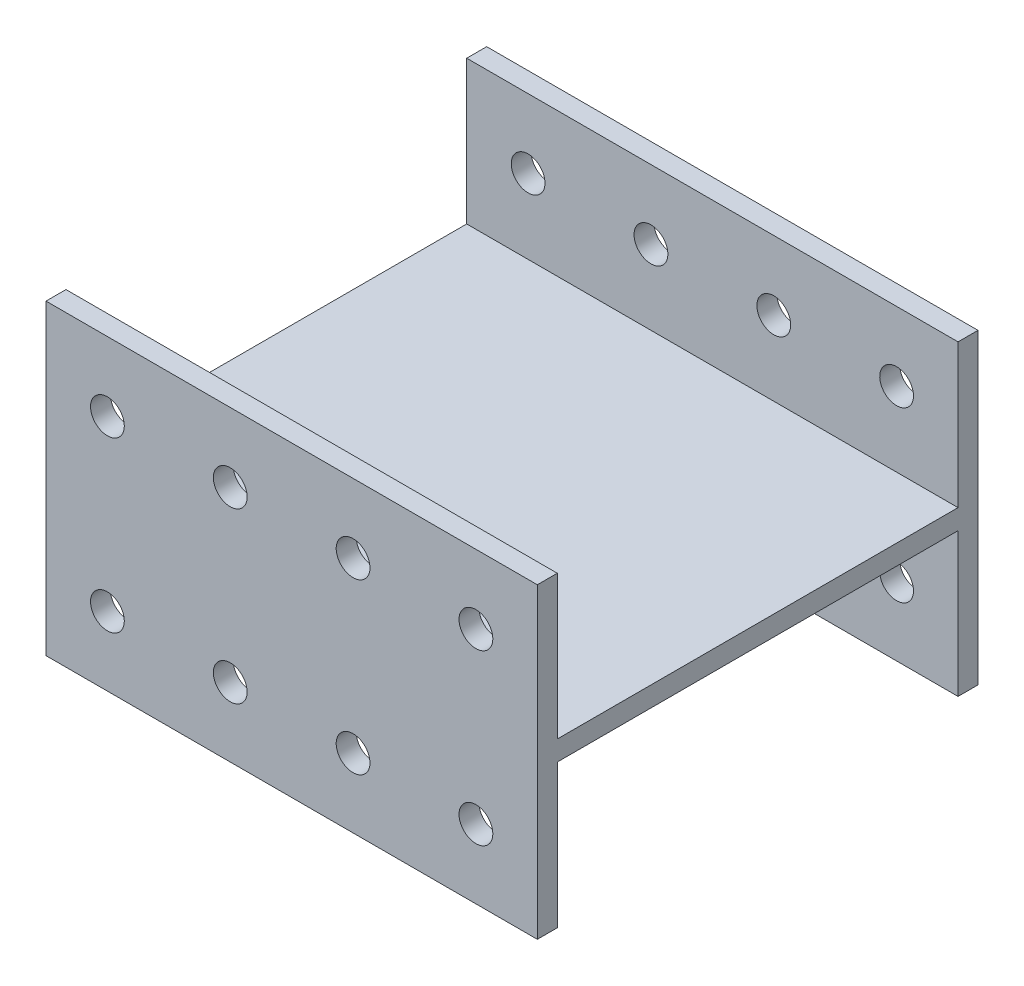
SolidWorks part; units mm, degrees
ref_plane "前视基准面" through (0, 0, 0) normal (0, 0, 1) x (1, 0, 0)
ref_plane "上视基准面" through (0, 0, 0) normal (0, 1, 0) x (1, 0, 0)
ref_plane "右视基准面" through (0, 0, 0) normal (1, 0, 0) x (0, 0, -1)
sketch "草图1" plane through (0, 0, 0) normal (0, 0, 1) x (1, 0, 0)
  line L1 (0, 200) -> (320, 200)
  line L2 (0, 200) -> (0, 0)
  line L3 (0, 0) -> (320, 0)
  line L4 (320, 200) -> (320, 0)
  dimension "D1" = 320
  dimension "D2" = 200
extrude "拉伸1" add sketch "草图1" along normal blind 287
sketch "草图2" plane through (0, 0, 287) normal (0, 0, 1) x (1, 0, 0)
  line L0 (0, 0) -> (320, 0) construction
  line L1 (0, 200) -> (0, 0) construction
  circle A0 centre (40, 45) radius 11
  dimension "D1" = 45
  dimension "D2" = 40
extrude "切除-拉伸1" cut sketch "草图2" against normal through all
pattern_linear "阵列(线性)1" count 4 spacing 80 along (1, 0, 0) count 2 spacing 110 along (0, 1, 0) of "切除-拉伸1"
sketch "草图6" plane through (0, 0, 0) normal (-1, 0, 0) x (0, 0, 1)
  line L1 (13, 200) -> (274, 200)
  line L2 (13, 200) -> (13, 106.5)
  line L3 (13, 106.5) -> (274, 106.5)
  line L4 (274, 200) -> (274, 106.5)
  line L7 (13, 0) -> (274, 0)
  line L8 (13, 0) -> (13, 93.5)
  line L9 (13, 93.5) -> (274, 93.5)
  line L10 (274, 0) -> (274, 93.5)
  line L12 (287, 200) -> (287, 0) construction
  line L13 (0, 200) -> (0, 0) construction
  dimension "D1" = 13
  dimension "D2" = 13
  dimension "D3" = 13
  dimension "D4" = 13
  dimension "D5" = 261
  dimension "D6" = 261
  dimension "D7" = 93.5
  dimension "D8" = 93.5
extrude "切除-拉伸3" cut sketch "草图6" against normal through all
